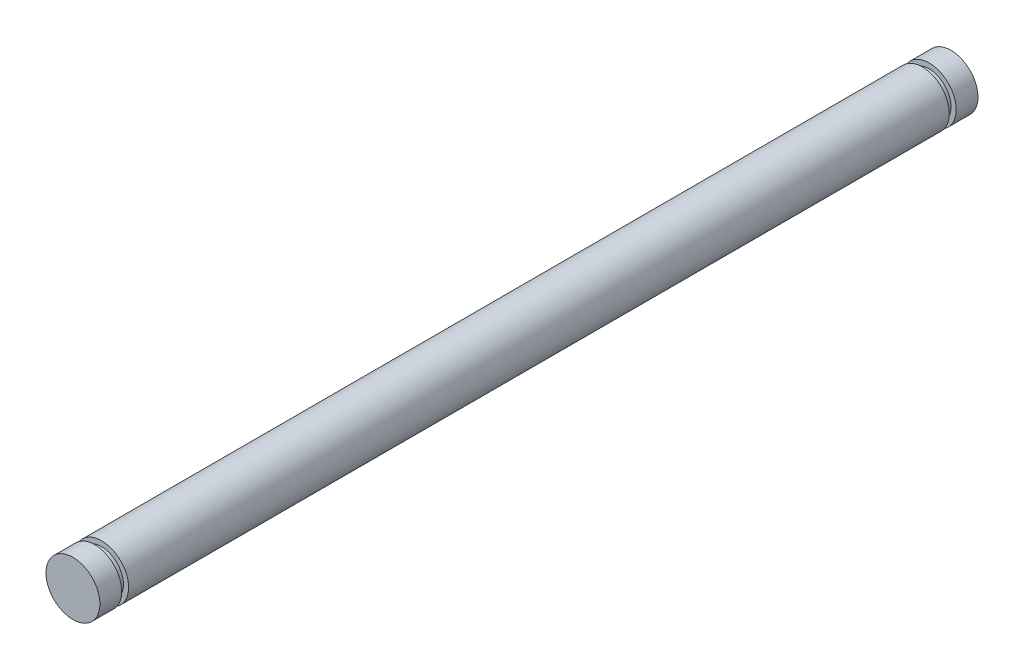
SolidWorks part; units mm, degrees
material "6061 Alloy"
ref_plane "Front Plane" through (0, 0, 0) normal (0, 0, 1) x (1, 0, 0)
ref_plane "Top Plane" through (0, 0, 0) normal (0, 1, 0) x (1, 0, 0)
ref_plane "Right Plane" through (0, 0, 0) normal (1, 0, 0) x (0, 0, -1)
sketch "Sketch1" plane through (0, 0, 0) normal (0, 0, 1) x (1, 0, 0)
  circle A0 centre (0, 0) radius 2
  dimension "D1" = 4
extrude "Boss-Extrude1" add sketch "Sketch1" along normal mid plane 65.0875
sketch "Sketch2" plane through (0, 0, 0) normal (1, 0, 0) x (0, 0, -1)
  line L0 (32.5437, 2) -> (-32.5437, 2) construction
  line L1 (-30.4165, 2) -> (-30.9245, 2)
  line L2 (-30.4165, 2) -> (-30.4165, 1.619)
  line L3 (-30.4165, 1.619) -> (-30.9245, 1.619)
  line L4 (-30.9245, 2) -> (-30.9245, 1.619)
  line L6 (-29.3687, 19.05) -> (-29.3687, 0) construction
  dimension "D1" = 1.0478
  dimension "D2" = 0.508
  dimension "D3" = 0.381
ref_axis "Axis1" through (0, 0, 32.5437) along (0, 0, -1)
revolve "Cut-Revolve1" cut sketch "Sketch2" angle 360 about axis through (0, 0, 32.5437) along (0, 0, -1)
mirror "Mirror1" about plane through (0, 0, 0) normal (0, 0, 1) of "Cut-Revolve1"
